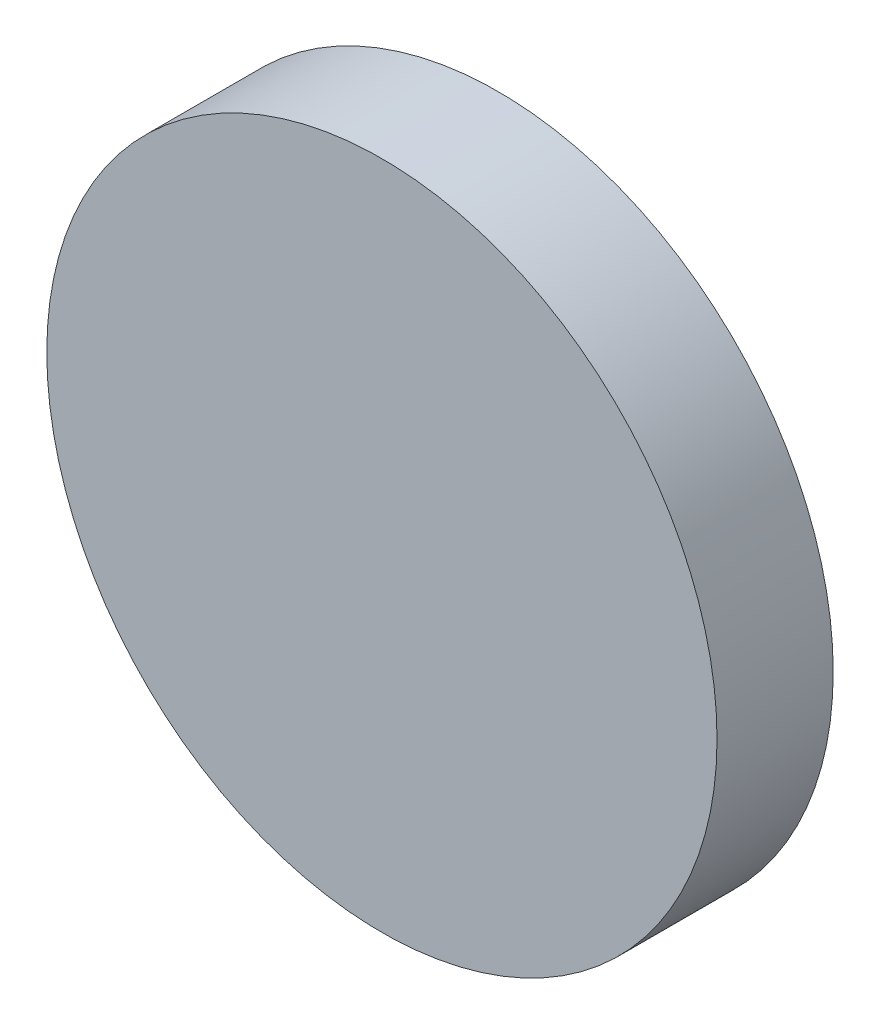
SolidWorks part; units mm, degrees
ref_plane "Front Plane" through (0, 0, 0) normal (0, 0, 1) x (1, 0, 0)
ref_plane "Top Plane" through (0, 0, 0) normal (0, 1, 0) x (1, 0, 0)
ref_plane "Right Plane" through (0, 0, 0) normal (1, 0, 0) x (0, 0, -1)
sketch "Sketch1" plane through (0, 0, 0) normal (0, 0, 1) x (1, 0, 0)
  circle A0 centre (0, 0) radius 47.625
  dimension "D1" = 95.25
extrude "Boss-Extrude1" add sketch "Sketch1" along normal blind 3.81
sketch "Sketch4" plane through (0, 0, 0) normal (0, 0, -1) x (-1, 0, 0)
  circle A0 centre (0, 0) radius 47.625
  circle A1 centre (0, 0) radius 44.45
  dimension "D1" = 88.9
extrude "Boss-Extrude2" add sketch "Sketch4" along normal blind 12.7
sketch "Sketch7" plane through (0, 0, 0) normal (0, 0, -1) x (-1, 0, 0)
  line L0 (-44.3842, -2.4176) -> (44.3842, -2.4176) construction
  line L1 (0, 44.45) -> (0, -43.7762) construction
  line L2 (-0.0792, -0.3493) -> (-0.0792, 44.1007) construction
  line L3 (-40.283, 5.5885) -> (40.1247, 5.5885) construction
  line L4 (-44.4782, 1.7785) -> (44.3199, 1.7785) construction
  line L5 (-40.283, 5.5885) -> (-44.4782, 1.7785) construction
  line L6 (40.1247, 5.5885) -> (44.3199, 1.7785) construction
  line L8 (-44.4546, -2.4176) -> (44.4454, -2.4176)
  line L9 (-44.4546, -2.4176) -> (-44.4546, -0.6396)
  line L10 (-44.4546, -0.6396) -> (44.4454, -0.6396)
  line L11 (44.4454, -2.4176) -> (44.4454, -0.6396)
  circle A0 centre (0, 0) radius 44.45 construction
  circle A1 centre (0, 0) radius 44.45 construction
  arc A2 (44.3199, 1.7785) -> (-44.4782, 1.7785) centre (-0.0792, -0.3493) ccw construction
  arc A3 (40.1247, 5.5885) -> (-40.283, 5.5885) centre (-0.0792, -0.3493) ccw construction
  point P19 (-44.459, -0.8936)
  dimension "D1" = 88.9
  dimension "D2" = 88.9
  dimension "D3" = 3.81
  dimension "D4" = 1.778
extrude "Boss-Extrude14" add sketch "Sketch7" along normal blind 5.08 contours L8 L11 L10 L9
equation "\"D1@Boss-Extrude1\"=0.15"
